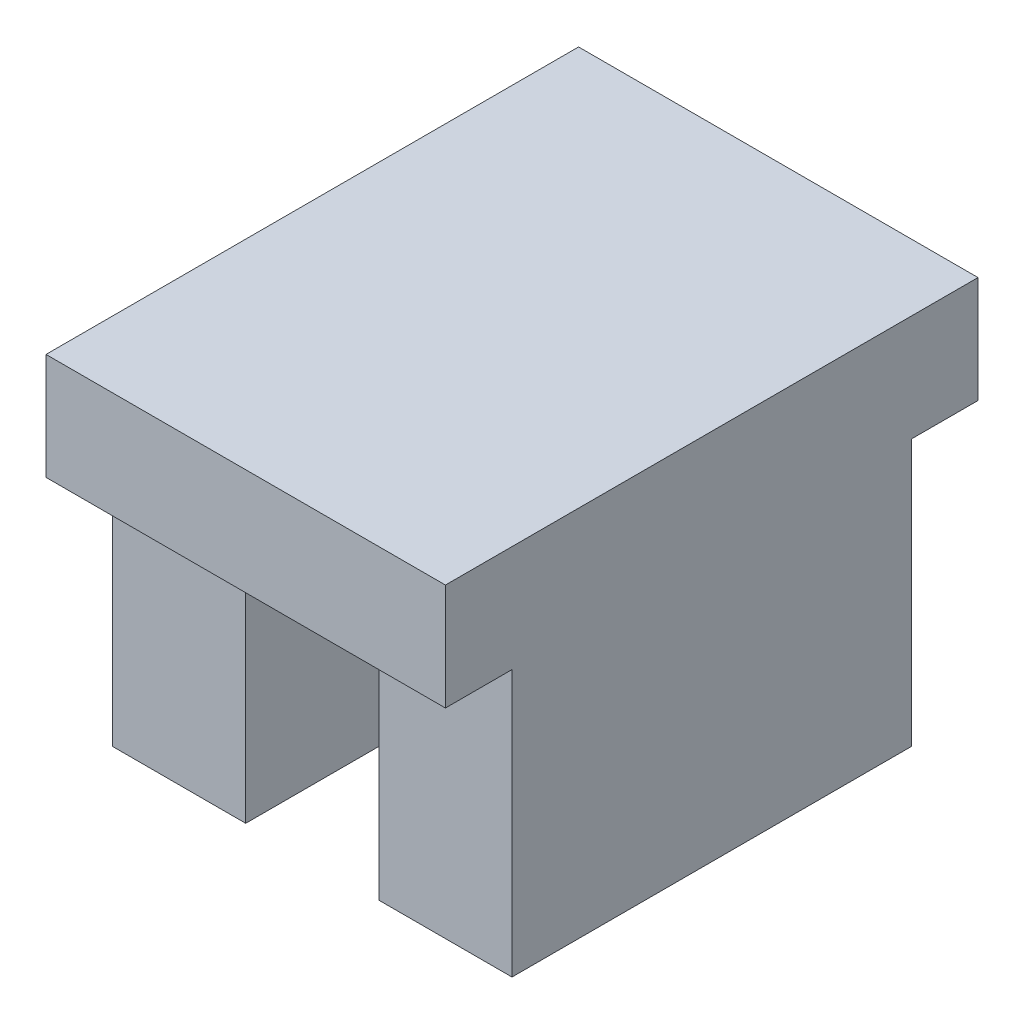
SolidWorks part; units mm, degrees
material "PW80:Mi:0:30:C1:0:1:2:Re:16:"
ref_plane "Plan1" through (0, 0, 0) normal (0, 0, 1) x (1, 0, 0)
ref_plane "Plan2" through (0, 0, 0) normal (0, 1, 0) x (1, 0, 0)
ref_plane "Plan3" through (0, 0, 0) normal (1, 0, 0) x (0, 0, -1)
sketch "Esquisse1" plane through (0, 0, 0) normal (0, 1, 0) x (1, 0, 0)
  line L1 (0, 0) -> (30, 0)
  line L2 (0, 0) -> (0, 40)
  line L3 (0, 40) -> (30, 40)
  line L4 (30, 0) -> (30, 40)
extrude "corps bouton poussoir" add sketch "Esquisse1" along normal blind 8
sketch "Esquisse2" plane through (0, 0, 0) normal (0, -1, 0) x (1, 0, 0)
  line L1 (10, -5) -> (0, -5)
  line L2 (10, -5) -> (10, -35)
  line L3 (10, -35) -> (0, -35)
  line L4 (0, -5) -> (0, -35)
  line L5 (30, -5) -> (20, -5)
  line L6 (30, -5) -> (30, -35)
  line L7 (30, -35) -> (20, -35)
  line L8 (20, -5) -> (20, -35)
extrude "2 contacts" add sketch "Esquisse2" along normal blind 20
